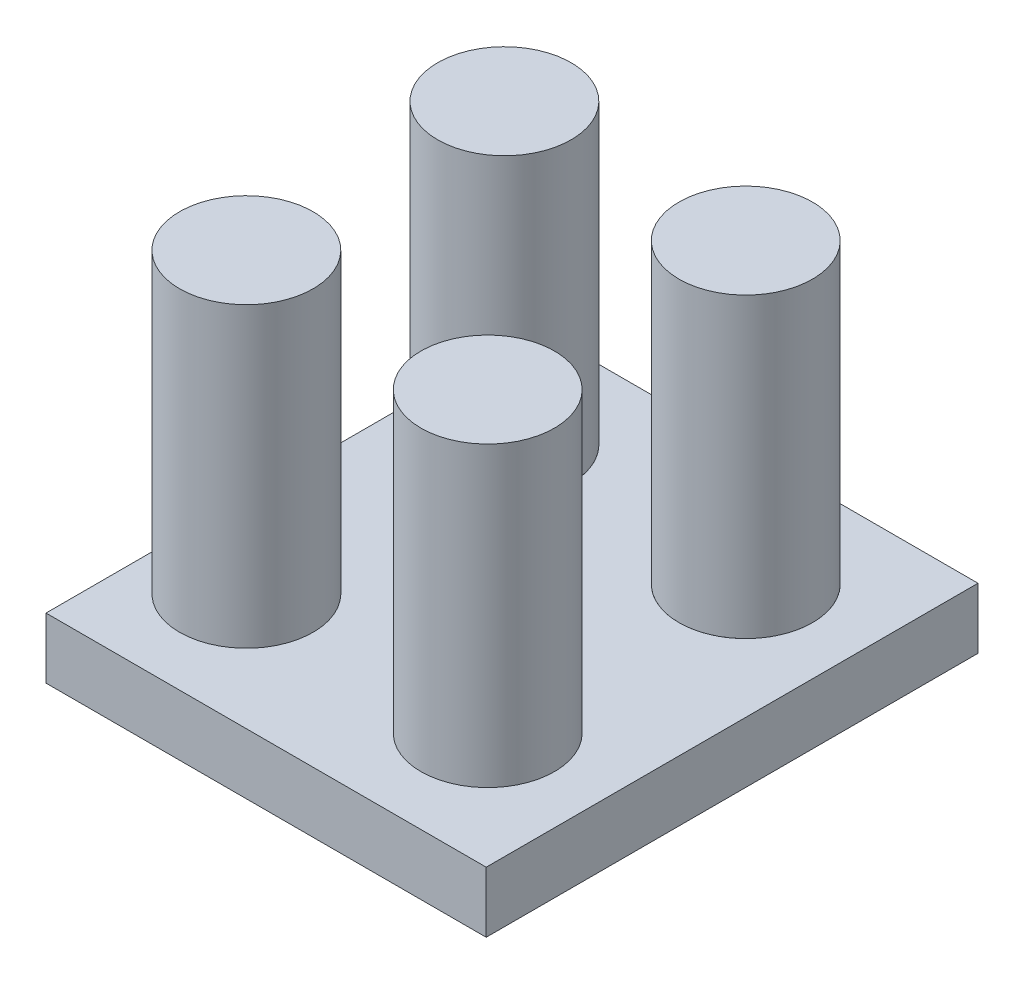
SolidWorks part; units mm, degrees
ref_plane "Front Plane" through (0, 0, 0) normal (0, 0, 1) x (1, 0, 0)
ref_plane "Top Plane" through (0, 0, 0) normal (0, 1, 0) x (1, 0, 0)
ref_plane "Right Plane" through (0, 0, 0) normal (1, 0, 0) x (0, 0, -1)
sketch "Sketch1" plane through (0, 0, 0) normal (0, 1, 0) x (1, 0, 0)
  line L0 (7.25, 0) -> (-7.25, 0) construction
  line L1 (-7.25, 8.1) -> (7.25, 8.1)
  line L2 (-7.25, 8.1) -> (-7.25, -8.1)
  line L3 (-7.25, -8.1) -> (7.25, -8.1)
  line L4 (7.25, 8.1) -> (7.25, -8.1)
  line L5 (-7.25, 8.1) -> (7.25, -8.1) construction
  line L6 (-7.25, -8.1) -> (7.25, 8.1) construction
  line L7 (7.25, -4.25) -> (3.45, -4.25) construction
  line L8 (3.45, -4.25) -> (3.45, -8.1) construction
  line L9 (3.45, -4.25) -> (-4.5, -4.25) construction
  circle A0 centre (3.45, -4.25) radius 2.2
  circle A1 centre (-4.5, -4.25) radius 2.2
  circle A2 centre (-4.5, 4.25) radius 2.2
  circle A3 centre (3.45, 4.25) radius 2.2
  point P0 (0, 0)
  dimension "D5" = 4.4
  dimension "D7" = 4.4
  dimension "D1" = 14.5
  dimension "D2" = 16.2
  dimension "D3" = 3.85
  dimension "D4" = 3.8
  dimension "D6" = 7.95
extrude "Boss-Extrude2" add sketch "Sketch1" along normal blind 2
sketch "Sketch2" plane through (0, 2, 0) normal (0, 1, 0) x (1, 0, 0)
  circle A0 centre (3.45, 4.25) radius 2.2
  circle A1 centre (-4.5, 4.25) radius 2.2
  circle A2 centre (3.45, -4.25) radius 2.2
  circle A3 centre (-4.5, -4.25) radius 2.2
extrude "Boss-Extrude3" add sketch "Sketch2" along normal blind 9.8 separate body
